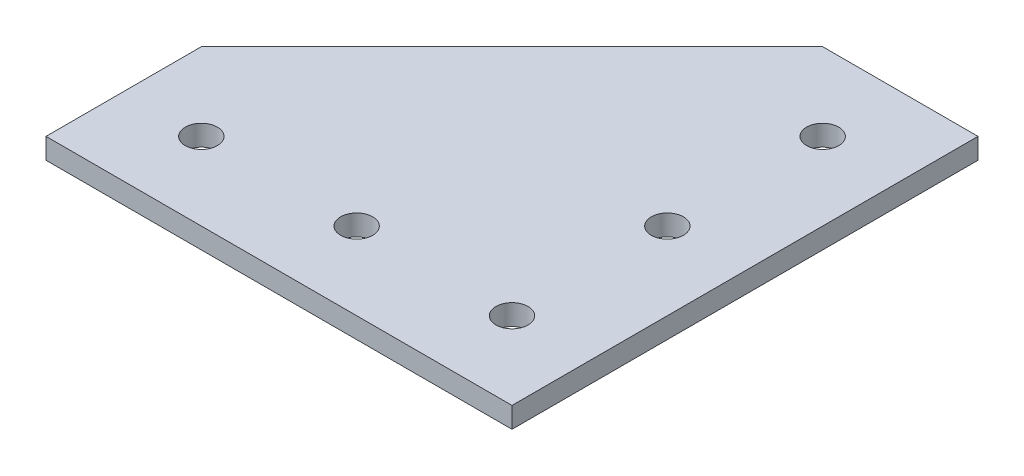
SolidWorks part; units mm, degrees
ref_plane "Front Plane" through (0, 0, 0) normal (0, 0, 1) x (1, 0, 0)
ref_plane "Top Plane" through (0, 0, 0) normal (0, 1, 0) x (1, 0, 0)
ref_plane "Right Plane" through (0, 0, 0) normal (1, 0, 0) x (0, 0, -1)
sketch "Sketch1" plane through (0, 0, 0) normal (0, 1, 0) x (1, 0, 0)
  line L5 (0, 0) -> (0, -90)
  line L6 (0, -90) -> (-90, -90)
  line L7 (-90, -90) -> (-90, -60)
  line L8 (0, 0) -> (-30, 0)
  line L9 (-30, 0) -> (-90, -60)
  circle A0 centre (-15, -15) radius 3.1
  circle A1 centre (-15, -45) radius 3.1
  circle A2 centre (-15, -75) radius 3.1
  circle A3 centre (-45, -75) radius 3.1
  circle A4 centre (-75, -75) radius 3.1
  dimension "D4" = 15
  dimension "D6" = 6.2
  dimension "D1" = 90
  dimension "D2" = 30
  dimension "D3" = 0
  dimension "D5" = 15
  dimension "D7" = 3
  dimension "D8" = 3
extrude "Boss-Extrude1" add sketch "Sketch1" along normal blind 4
